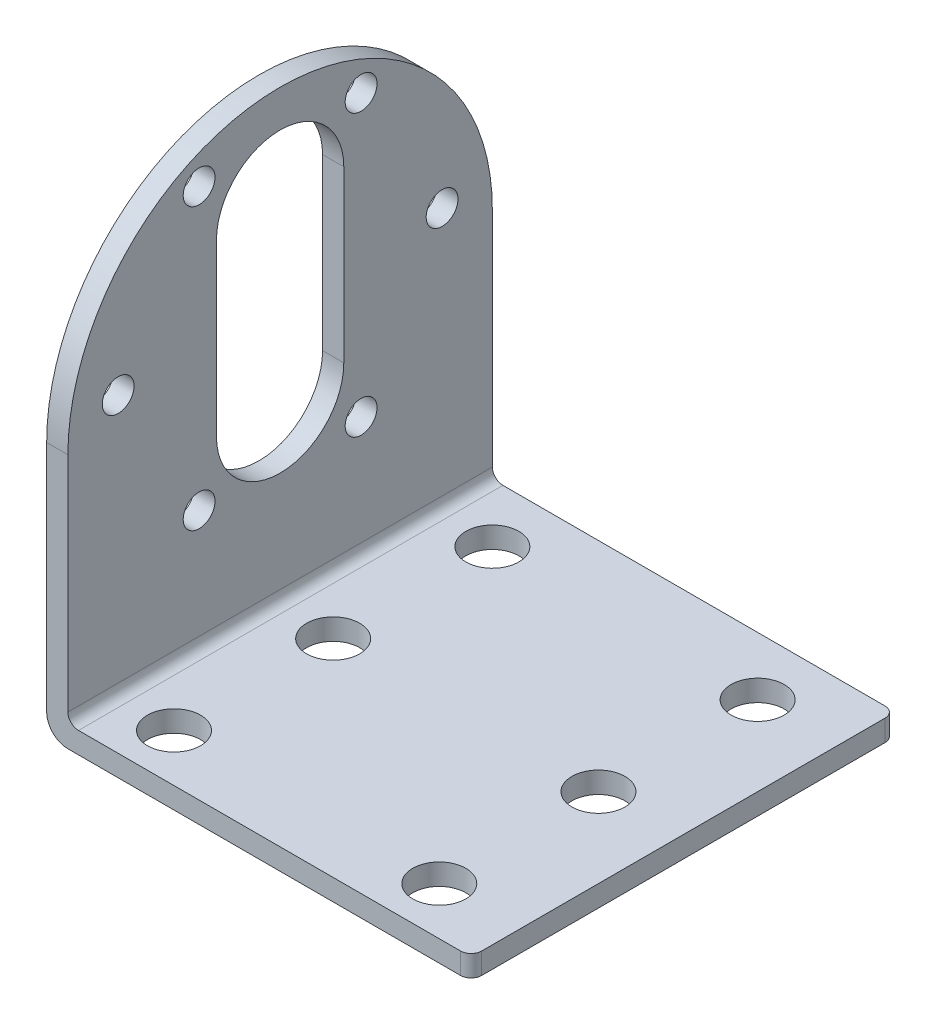
SolidWorks part; units mm, degrees
material "Ductile Iron"
ref_plane "Front Plane" through (0, 0, 0) normal (0, 0, 1) x (1, 0, 0)
ref_plane "Top Plane" through (0, 0, 0) normal (0, 1, 0) x (1, 0, 0)
ref_plane "Right Plane" through (0, 0, 0) normal (1, 0, 0) x (0, 0, -1)
sketch "Sketch2" plane through (0, 0, 0) normal (0, 0, 1) x (1, 0, 0)
  line L0 (2, 0) -> (40, 0)
  line L1 (0, 2) -> (0, 45)
  line L2 (2, 3) -> (2, 45)
  line L3 (3, 2) -> (40, 2)
  line L4 (40, 2) -> (40, 0)
  line L5 (0, 45) -> (2, 45)
  line L6 (2, 2) -> (40, 2) construction
  line L7 (2, 2) -> (2, 45) construction
  line L8 (0, 0) -> (40, 0) construction
  line L9 (0, 0) -> (0, 45) construction
  arc A0 (3, 2) -> (2, 3) centre (3, 3) cw
  arc A1 (2, 0) -> (0, 2) centre (2, 2) cw
  point P13 (0, 0)
  dimension "D4" = 1
  dimension "D5" = 2
  dimension "D1" = 40
  dimension "D3" = 45
  dimension "D2" = 2
extrude "Boss-Extrude1" add sketch "Sketch2" along normal blind 40
hole_wizard "Hole1" positions "Sketch3" profile "Sketch4" legacy end condition through all
sketch "Sketch3" plane through (0, 2, 0) normal (0, 1, 0) x (1, 0, 0)
  line L0 (40, -40) -> (3, -40) construction
  point P0 (32.5, -35.5)
  point P6 (32.5, -5.5)
  point P9 (7.5, -5.5)
  point P11 (7.5, -35.5)
  dimension "D1" = 4.5
  dimension "D2" = 7.5
  dimension "D3" = 30
  dimension "D4" = 25
sketch "Sketch4" plane through (32.5, 2, 35.5) normal (1, 0, 0) x (0, 0, 1)
  line L0 (0, 0) -> (0, 2)
  line L1 (0, 2) -> (2.5, 2)
  line L2 (2.5, 2) -> (2.5, 0)
  line L3 (2.5, 0) -> (0, 0)
  line L4 (0, 110) -> (0, -10) construction
  dimension "Diameter" = 5
  dimension "Depth" = 2
sketch "Sketch5" plane through (2, 0, 0) normal (1, 0, 0) x (0, 0, -1)
  line L0 (-40, 3) -> (-40, 45) construction
  line L1 (-40, 3) -> (-40, 45)
  line L2 (0, 3) -> (0, 45) construction
  line L3 (0, 3) -> (0, 45)
  line L4 (-40, 24) -> (-40, 3)
  line L5 (0, 3) -> (0, 24)
  arc A0 (-40, 24) -> (0, 24) centre (-20, 24) cw
  line M2 (0, 45) -> (-40, 45)
  line M3 (-40, 45) -> (-40, 3)
  dimension "D1" = 20
extrude "Cut-Extrude1" cut sketch "Sketch5" against normal blind 40 contours A0 L3 M3 M2
sketch "Sketch6" plane through (2, 0, 0) normal (1, 0, 0) x (0, 0, -1)
  line L0 (-20, 34.5) -> (-20, 18.5) construction
  line L1 (-14, 34.5) -> (-14, 18.5)
  line L2 (-26, 34.5) -> (-26, 18.5)
  arc A0 (-14, 34.5) -> (-26, 34.5) centre (-20, 34.5) ccw
  arc A1 (-26, 18.5) -> (-14, 18.5) centre (-20, 18.5) ccw
  arc A2 (0, 24) -> (-40, 24) centre (-20, 24) ccw construction
  circle A3 centre (-20, 26.5) radius 15 construction
  point P3 (-20, 26.5)
  point P8 (-20, 40.5)
  point P9 (-20, 12.5)
  point P13 (-20, 44)
  dimension "D3" = 6
  dimension "D4" = 30
  dimension "D1" = 28
  dimension "D2" = 9.5
extrude "Cut-Extrude2" cut sketch "Sketch6" against normal blind 40
sketch "Sketch7" plane through (2, 0, 0) normal (1, 0, 0) x (0, 0, -1)
  line L0 (-20, 40.5) -> (-20, 12.5) construction
  line L1 (-35.265, 26.5) -> (-20, 26.5) construction
  line L2 (-20, 26.5) -> (-27.6325, 13.2801) construction
  arc A0 (-14, 34.5) -> (-26, 34.5) centre (-20, 34.5) ccw construction
  arc A1 (-26, 18.5) -> (-14, 18.5) centre (-20, 18.5) ccw construction
  circle A2 centre (-20, 26.5) radius 15.265 construction
  circle A3 centre (-4.735, 26.5) radius 1.5
  circle A4 centre (-35.265, 26.5) radius 1.5
  circle A5 centre (-27.6325, 13.2801) radius 1.5
  circle A6 centre (-12.3675, 13.2801) radius 1.5
  circle A7 centre (-27.6325, 39.7199) radius 1.5
  circle A8 centre (-12.3675, 39.7199) radius 1.5
  dimension "D1" = 30.53
  dimension "D2" = 3
  dimension "D3" = 3
  dimension "D4" = 3
  dimension "D6" = 3
  dimension "D7" = 3
  dimension "D8" = 3
  dimension "D5" = 60
extrude "Cut-Extrude3" cut sketch "Sketch7" against normal blind 40
fillet "Fillet1" radius 1 2 edges at (40, 1, 0) (40, 1, 40)
sketch "Sketch10" plane through (0, 2, 0) normal (0, 1, 0) x (1, 0, 0)
  line L0 (7.5, -3) -> (7.5, -38) construction
  line L1 (32.5, -3) -> (32.5, -38) construction
  circle A0 centre (7.5, -5.5) radius 2.5 construction
  circle A1 centre (7.5, -35.5) radius 2.5 construction
  circle A2 centre (32.5, -5.5) radius 2.5 construction
  circle A3 centre (32.5, -35.5) radius 2.5 construction
  circle A4 centre (7.5, -20.5) radius 2.5
  circle A5 centre (32.5, -20.5) radius 2.5
  dimension "D1" = 5
  dimension "D2" = 5
extrude "Cut-Extrude4" cut sketch "Sketch10" against normal blind 40
